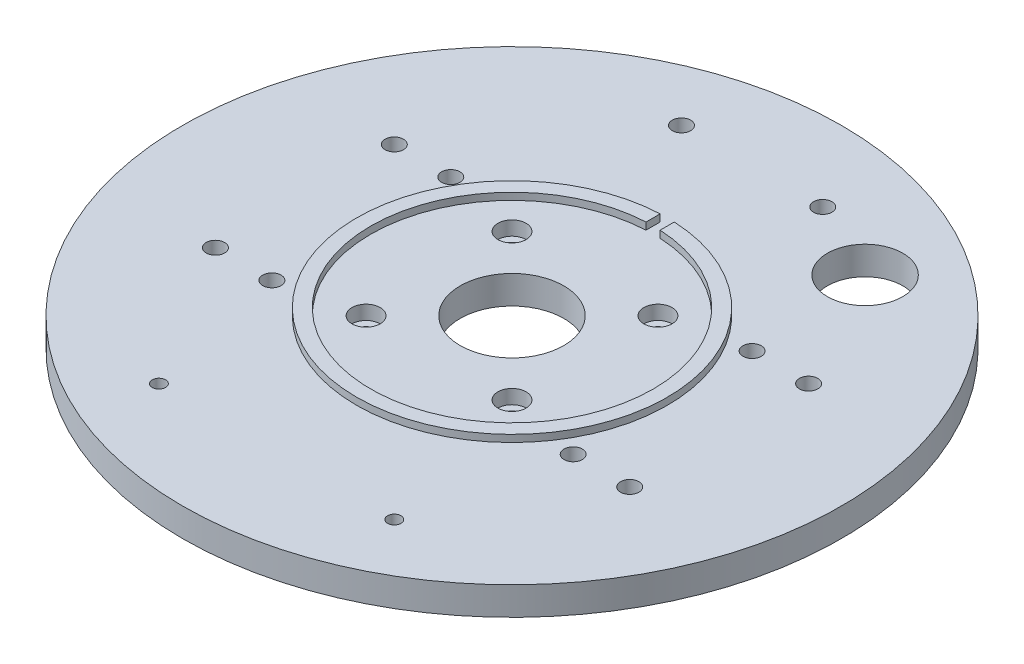
SolidWorks part; units mm, degrees
ref_plane "Front Plane" through (0, 0, 0) normal (0, 0, 1) x (1, 0, 0)
ref_plane "Top Plane" through (0, 0, 0) normal (0, 1, 0) x (1, 0, 0)
ref_plane "Right Plane" through (0, 0, 0) normal (1, 0, 0) x (0, 0, -1)
sketch "Sketch1" plane through (0, 0, 0) normal (0, 1, 0) x (1, 0, 0)
  circle A0 centre (0, 0) radius 11
  circle A1 centre (0, 0) radius 70
  point P0 (0, 0)
  dimension "D1" = 140
extrude "Boss-Extrude1" add sketch "Sketch1" along normal blind 6 contours A1 A0
sketch "Sketch2" plane through (0, 6, 0) normal (0, 1, 0) x (1, 0, 0)
  circle A0 centre (-15.5, 15.5) radius 1.42
  circle A1 centre (15.5, 15.5) radius 1.42
  circle A2 centre (15.5, -15.5) radius 1.42
  circle A3 centre (-15.5, -15.5) radius 1.42
  dimension "D3" = 2.84
  dimension "D1" = 15.5
  dimension "D2" = 15.5
  dimension "D4" = 2
  dimension "D5" = 2
extrude "Cut-Extrude2" cut sketch "Sketch2" against normal blind 10
sketch "Sketch3" plane through (0, 0, 0) normal (0, 1, 0) x (1, 0, 0)
  line L0 (-49.3955, 65) -> (75.3146, 65) construction
  line L1 (65, 69.9962) -> (65, -101.8873) construction
  line L2 (-65, 92.0385) -> (-65, -105.1702) construction
  line L3 (0, -54.2591) -> (0, 50.4974) construction
  dimension "D1" = 65
  dimension "D2" = 65
  dimension "D3" = 65
sketch "Sketch4" plane through (0, 6, 0) normal (0, 1, 0) x (1, 0, 0)
  circle A0 centre (-15.5, 15.5) radius 3
  circle A1 centre (15.5, 15.5) radius 3
  circle A3 centre (15.5, -15.5) radius 3
  circle A4 centre (-15.5, -15.5) radius 3
  dimension "D1" = 6
  dimension "D2" = 6
  dimension "D3" = 6
  dimension "D4" = 6
extrude "Cut-Extrude3" cut sketch "Sketch4" against normal blind 3
sketch "Sketch5" plane through (0, 6, 0) normal (0, 1, 0) x (1, 0, 0)
  line L0 (0, 46.5441) -> (0, -51.9418) construction
  circle A0 centre (-32, 19) radius 1.95
  circle A1 centre (-44, 19) radius 1.95
  circle A2 centre (-44, -19) radius 1.95
  circle A3 centre (-32, -19) radius 1.95
  circle A4 centre (32, -19) radius 1.95
  circle A5 centre (44, -19) radius 1.95
  circle A6 centre (44, 19) radius 1.95
  circle A7 centre (32, 19) radius 1.95
  dimension "D3" = 3.9
  dimension "D1" = 19
  dimension "D2" = 32
  dimension "D6" = 38
  dimension "D7" = 12
  dimension "D4" = 2
  dimension "D5" = 2
extrude "Cut-Extrude4" cut sketch "Sketch5" against normal blind 10
sketch "Sketch6" plane through (0, 6, 0) normal (0, 1, 0) x (1, 0, 0)
  circle A0 centre (13, 29) radius 1.95
  circle A3 centre (13, 53) radius 1.95
  circle A4 centre (-17, 52.9998) radius 1.95
  dimension "D3" = 3.9
  dimension "D4" = 3.9
  dimension "D7" = 3.9
  dimension "D1" = 13
  dimension "D2" = 29
  dimension "D5" = 24
  dimension "D6" = 30
  dimension "D8" = 13
extrude "Cut-Extrude5" cut sketch "Sketch6" against normal blind 6
sketch "Sketch7" plane through (0, 6, 0) normal (0, 1, 0) x (1, 0, 0)
  circle A0 centre (-25, -50) radius 1.42
  circle A1 centre (25, -50) radius 1.42
  dimension "D5" = 2.84
  dimension "D6" = 2.84
  dimension "D1" = 25
  dimension "D2" = 25
  dimension "D3" = 50
  dimension "D4" = 50
extrude "Cut-Extrude6" cut sketch "Sketch7" against normal blind 10
sketch "Sketch8" plane through (0, 6, 0) normal (0, 1, 0) x (1, 0, 0)
  circle A0 centre (30, 45) radius 8
  dimension "D3" = 16
  dimension "D1" = 30
  dimension "D2" = 45
extrude "Cut-Extrude7" cut sketch "Sketch8" against normal blind 10
sketch "Sketch9" plane through (0, 6, 0) normal (0, 1, 0) x (1, 0, 0)
  circle A0 centre (0, 0) radius 33
  circle A1 centre (0, 0) radius 30
  dimension "D1" = 66
  dimension "D2" = 60
extrude "Boss-Extrude2" add sketch "Sketch9" along normal blind 1.5
sketch "Sketch10" plane through (0, 7.5, 0) normal (0, 1, 0) x (1, 0, 0)
  line L1 (-1.5, 26.2042) -> (1.5, 26.2042)
  line L2 (-1.5, 26.2042) -> (-1.5, 37.066)
  line L3 (-1.5, 37.066) -> (1.5, 37.066)
  line L4 (1.5, 26.2042) -> (1.5, 37.066)
  line L5 (-1.5, 26.2042) -> (1.5, 37.066) construction
  line L6 (-1.5, 37.066) -> (1.5, 26.2042) construction
  point P0 (0, 31.6351)
  dimension "D1" = 3
  dimension "D2" = 0
extrude "Cut-Extrude9" cut sketch "Sketch10" along direction (0, 1, 0) on the side against the normal up to surface (1.5 mm away)
sketch "Sketch11" plane through (0, 6, 0) normal (0, 1, 0) x (1, 0, 0)
  circle A0 centre (13, 29) radius 2.4712
extrude "Boss-Extrude3" add sketch "Sketch11" against normal blind 1
